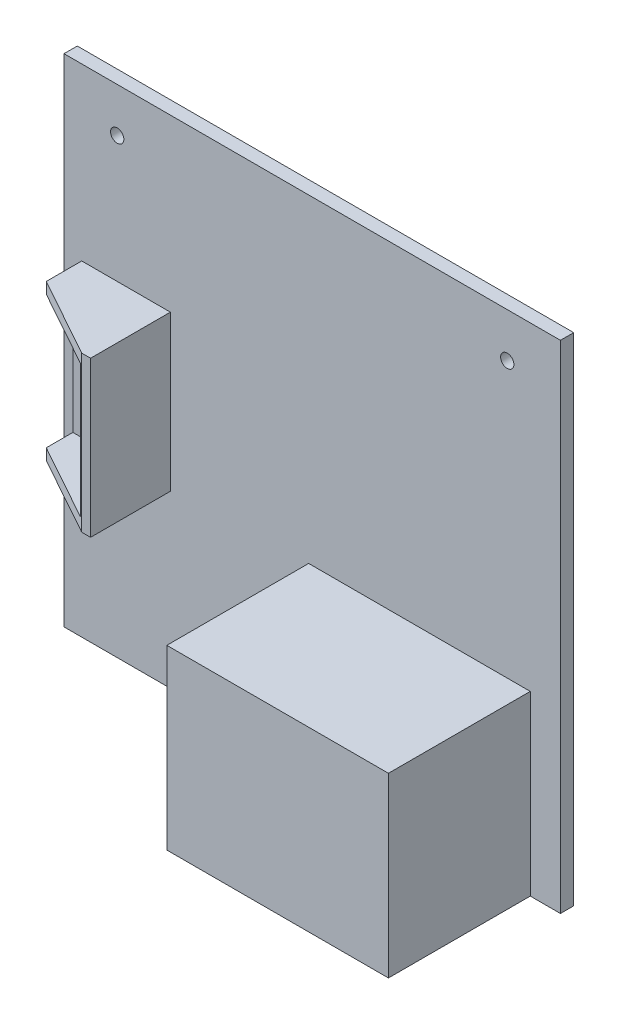
SolidWorks part; units mm, degrees
ref_plane "Alzado" through (0, 0, 0) normal (0, 0, 1) x (1, 0, 0)
ref_plane "Planta" through (0, 0, 0) normal (0, 1, 0) x (1, 0, 0)
ref_plane "Vista lateral" through (0, 0, 0) normal (1, 0, 0) x (0, 0, -1)
sketch "Croquis1" plane through (0, 0, 0) normal (0, 0, 1) x (1, 0, 0)
  line L1 (-56, -56) -> (56, -56)
  line L2 (-56, -56) -> (-56, 56)
  line L3 (-56, 56) -> (56, 56)
  line L4 (56, -56) -> (56, 56)
  line L5 (-56, -56) -> (56, 56) construction
  line L6 (-56, 56) -> (56, -56) construction
  point P0 (0, 0)
  dimension "D1" = 112
  dimension "D2" = 112
extrude "Saliente-Extruir1" add sketch "Croquis1" along normal blind 3
sketch "Croquis2" plane through (0, 0, 3) normal (0, 0, 1) x (1, 0, 0)
  line L0 (56, -56) -> (49.197, -56)
  line L1 (-56, -56) -> (56, -56) construction
  line L3 (49.197, -56) -> (-0.803, -56)
  line L4 (49.197, -56) -> (49.197, -16)
  line L5 (49.197, -16) -> (-0.803, -16)
  line L6 (-0.803, -56) -> (-0.803, -16)
  line M7 (-56, -56) -> (56, -56)
  dimension "D1" = 6.803
  dimension "D2" = 40
  dimension "D3" = 50
extrude "Saliente-Extruir2" add sketch "Croquis2" along normal blind 32 contours L6 L4 L5 M7
sketch "Croquis3" plane through (0, 0, 3) normal (0, 0, 1) x (1, 0, 0)
  line L0 (-42, -56) -> (-42, -17.5)
  line L1 (-56, -56) -> (-0.803, -56) construction
  line L2 (-52, -17.5) -> (-32, -17.5)
  line L3 (-56, 56) -> (-56, -56) construction
  line L4 (-52, -17.5) -> (-52, 17.5)
  line L5 (-52, 17.5) -> (-32, 17.5)
  line L6 (-32, 17.5) -> (-32, -17.5)
  point P7 (-42, -17.5)
  dimension "D1" = 38.5
  dimension "D2" = 20
  dimension "D3" = 4
  dimension "D4" = 35
extrude "Saliente-Extruir3" add sketch "Croquis3" along normal blind 18 contours L6 L2 L4 L5
sketch "Croquis4" plane through (0, 0, 21) normal (0, 0, 1) x (1, 0, 0)
  line L0 (-52, 15) -> (-34.5, 15)
  line L1 (-52, -17.5) -> (-52, 17.5) construction
  line L2 (-34.5, 15) -> (-34.5, -15)
  line L3 (-34.5, -15) -> (-52, -15)
  line L4 (-52, -17.5) -> (-52, 17.5) construction
  line L5 (-52, -15) -> (-52, 15)
  line L6 (-52, 17.5) -> (-32, 17.5) construction
  line L7 (-32, 17.5) -> (-32, -17.5) construction
  line L8 (-52, -17.5) -> (-32, -17.5) construction
  dimension "D1" = 2.5
  dimension "D2" = 2.5
  dimension "D3" = 2.5
extrude "Cortar-Extruir1" cut sketch "Croquis4" against normal blind 16
sketch "Croquis5" plane through (0, -17.5, 0) normal (0, -1, 0) x (1, 0, 0)
  line L0 (-52, 3) -> (-52, 11)
  line L1 (-52, 21) -> (-52, 3) construction
  line L2 (-52, 11) -> (-34.0003, 21)
  line L3 (-52, 21) -> (-32, 21) construction
  line L4 (-34.0003, 21) -> (-52, 21)
  line L5 (-52, 21) -> (-52, 11)
  line M5 (-32, 21) -> (-52, 21)
  line M6 (-52, 21) -> (-52, 3)
  dimension "D1" = 8
  dimension "D2" = 20.591
extrude "Cortar-Extruir2" cut sketch "Croquis5" against normal blind 46 contours L2 M6 M5
sketch "Croquis6" plane through (0, 0, 3) normal (0, 0, 1) x (1, 0, 0)
  line L0 (-56, 56) -> (-56, -56) construction
  line L1 (56, 56) -> (-56, 56) construction
  line L2 (-0.803, -56) -> (-0.803, -16) construction
  line L3 (-56, -56) -> (-0.803, -56) construction
  circle A0 centre (-44, 46) radius 1.5
  circle A1 centre (44, 46) radius 1.5
  circle A2 centre (-6.803, -46) radius 1.5
  dimension "D1" = 12
  dimension "D4" = 3
  dimension "D6" = 10
  dimension "D2" = 88
  dimension "D3" = 10
  dimension "D5" = 6
extrude "Cortar-Extruir3" cut sketch "Croquis6" against normal blind 46
